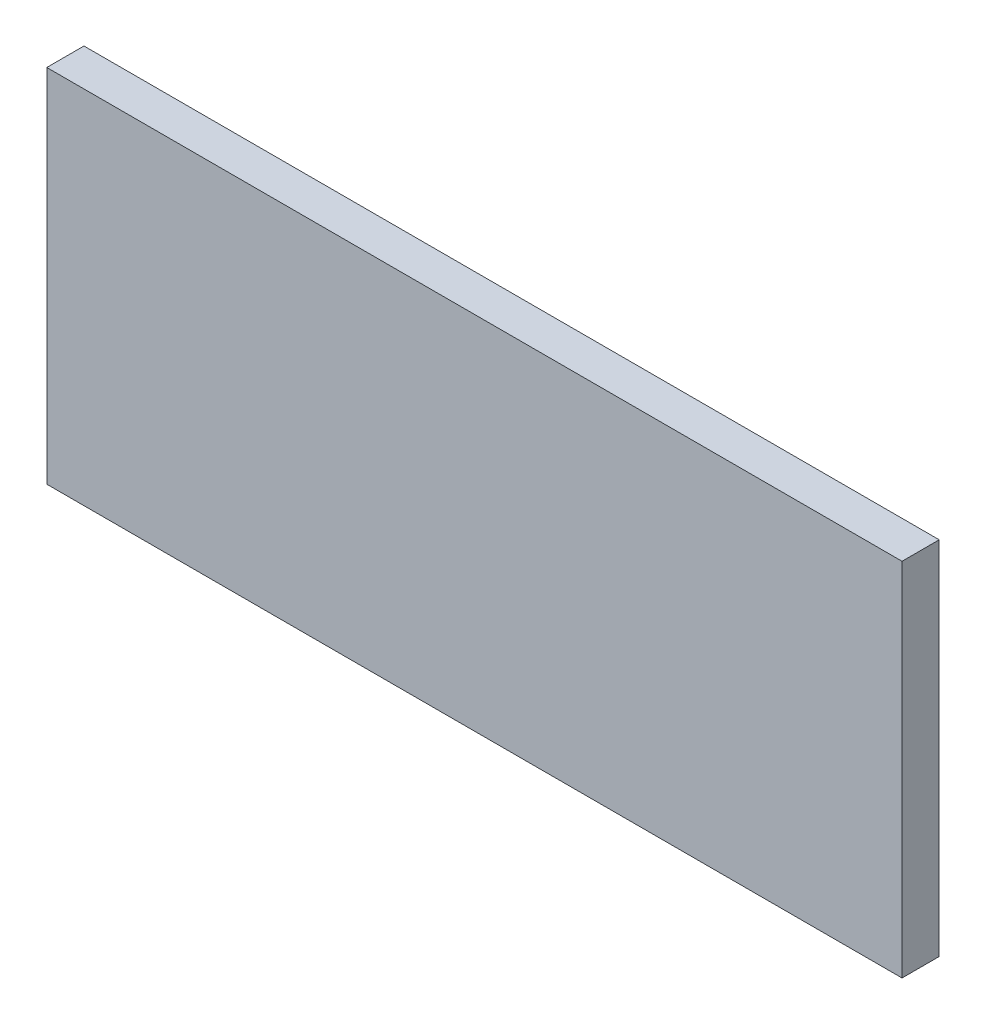
SolidWorks part; units mm, degrees
material "Glass"
ref_plane "Front Plane" through (0, 0, 0) normal (0, 0, 1) x (1, 0, 0)
ref_plane "Top Plane" through (0, 0, 0) normal (0, 1, 0) x (1, 0, 0)
ref_plane "Right Plane" through (0, 0, 0) normal (1, 0, 0) x (0, 0, -1)
sketch "Sketch1" plane through (0, 0, 0) normal (0, 0, 1) x (1, 0, 0)
  line L0 (-1726.9103, 2322.9236) -> (2873.0897, 2322.9236)
  line L1 (2873.0897, 2322.9236) -> (2873.0897, 381.7336)
  line L2 (2873.0897, 381.7336) -> (-1726.9103, 381.7336)
  line L3 (-1726.9103, 381.7336) -> (-1726.9103, 2322.9236)
  dimension "D1" = 4600
  dimension "D2" = 1941.19
extrude "Boss-Extrude1" add sketch "Sketch1" along normal blind 200
